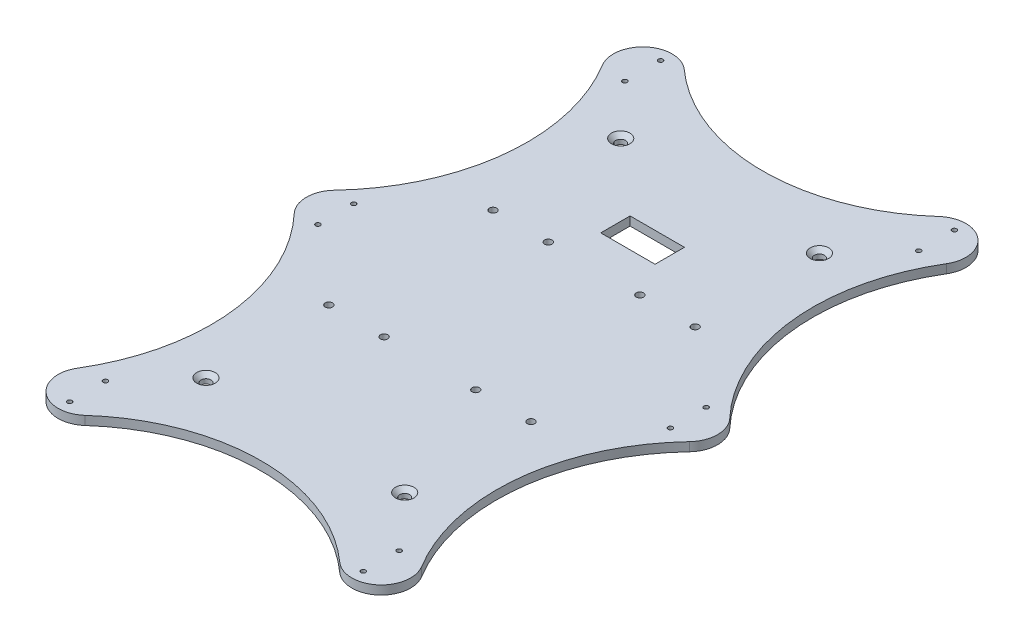
SolidWorks part; units mm, degrees
ref_plane "Front Plane" through (0, 0, 0) normal (0, 0, 1) x (1, 0, 0)
ref_plane "Top Plane" through (0, 0, 0) normal (0, 1, 0) x (1, 0, 0)
ref_plane "Right Plane" through (0, 0, 0) normal (1, 0, 0) x (0, 0, -1)
sketch "Sketch1" plane through (0, 0, 0) normal (0, 1, 0) x (1, 0, 0)
  line L0 (0, 85.4011) -> (0, -85.4011) construction
  line L5 (-25, 0) -> (0, 0) construction
  line L7 (-34.4, -27.95) -> (-15.6, -27.95) construction
  line L8 (0, 85.4011) -> (-22.7784, 85.4011) construction
  line L9 (-60, 0) -> (-60, -6.09) construction
  line L10 (-50, 94.5197) -> (-50, 88.4297) construction
  line L11 (-60, 0) -> (-83.5337, 0) construction
  line L12 (-50, 94.5197) -> (-65.6253, 94.5197) construction
  line L21 (-34.4, -27.95) -> (-34.4, 27.95) construction
  line L27 (-34.4, 27.95) -> (-15.6, 27.95) construction
  line L28 (-15.6, -27.95) -> (-15.6, 27.95) construction
  line L31 (-34.4, -27.95) -> (-15.6, 27.95) construction
  line L32 (-34.4, 27.95) -> (-15.6, -27.95) construction
  arc A4 (-43.3281, 101.9685) -> (43.3281, 101.9685) centre (0, 150.342) ccw
  arc A5 (58.5478, 89.3297) -> (43.3281, 101.9685) centre (50, 94.5197) ccw
  arc A6 (67.2725, -6.8637) -> (67.2725, 6.8637) centre (60, 0) ccw
  arc A7 (58.5478, 89.3297) -> (67.2725, 6.8637) centre (117.0279, 53.8223) ccw
  arc A8 (58.5478, -89.3297) -> (67.2725, -6.8637) centre (117.0279, -53.8223) cw
  arc A9 (58.5478, -89.3297) -> (43.3281, -101.9685) centre (50, -94.5197) cw
  arc A10 (-43.3281, -101.9685) -> (43.3281, -101.9685) centre (0, -150.342) cw
  arc A11 (-58.5478, -89.3297) -> (-43.3281, -101.9685) centre (-50, -94.5197) ccw
  arc A12 (-58.5478, -89.3297) -> (-67.2725, -6.8637) centre (-117.0279, -53.8223) ccw
  arc A13 (-58.5478, 89.3297) -> (-67.2725, 6.8637) centre (-117.0279, 53.8223) cw
  arc A14 (-67.2725, -6.8637) -> (-67.2725, 6.8637) centre (-60, 0) cw
  arc A15 (-58.5478, 89.3297) -> (-43.3281, 101.9685) centre (-50, 94.5197) cw
  circle A16 centre (-60, -6.09) radius 0.7937
  circle A17 centre (-50, 88.4297) radius 0.7937
  circle A18 centre (-50, 100.6097) radius 0.7937
  circle A19 centre (-60, 6.09) radius 0.7937
  circle A20 centre (60, 6.09) radius 0.7937
  circle A21 centre (60, -6.09) radius 0.7937
  circle A22 centre (50, 88.4297) radius 0.7937
  circle A23 centre (50, 100.6097) radius 0.7937
  circle A24 centre (50, -88.4297) radius 0.7937
  circle A25 centre (50, -100.6097) radius 0.7937
  circle A26 centre (-50, -88.4297) radius 0.7937
  circle A27 centre (-50, -100.6097) radius 0.7937
  circle A28 centre (-34.4, 27.95) radius 1.25
  circle A29 centre (-15.6, 27.95) radius 1.25
  circle A30 centre (-34.4, -27.95) radius 1.25
  circle A31 centre (-15.6, -27.95) radius 1.25
  circle A32 centre (15.6, -27.95) radius 1.25
  circle A33 centre (34.4, -27.95) radius 1.25
  circle A34 centre (15.6, 27.95) radius 1.25
  circle A35 centre (34.4, 27.95) radius 1.25
  point P0 (-25, 0)
  dimension "D1" = 18.8
  dimension "D3" = 20
  dimension "D4" = 25
  dimension "D7" = 1.5875
  dimension "D8" = 1.5875
  dimension "D14" = 6.09
  dimension "D15" = 6.09
  dimension "D5" = 2.5
  dimension "D13" = 6.09
  dimension "D2" = 55.9
  dimension "D6" = 6.09
  dimension "D9" = 6.09
  dimension "D10" = 6.09
  dimension "D11" = 6.09
  dimension "D12" = 6.09
  dimension "D16" = 6.09
extrude "Boss-Extrude1" add sketch "Sketch1" along normal blind 3
sketch "Sketch2" plane through (0, 3, 0) normal (0, 1, 0) x (1, 0, 0)
  point P0 (33.8292, 70.8368)
  point P1 (-33.8292, 70.8368)
  point P2 (33.8292, -70.3632)
  point P3 (-33.8292, -70.3632)
hole_wizard "CSK for M3 Flat Head Machine Screw1" positions "Sketch3" profile "Sketch4" countersink size "M3" standard "ANSI Metric" end condition through all
sketch "Sketch3" plane through (0, 3, 0) normal (0, 1, 0) x (1, 0, 0)
  point P0 (-33.8292, 70.8368)
  point P3 (33.8292, 70.8368)
  point P6 (-33.8292, -70.3632)
  point P9 (33.8292, -70.3632)
sketch "Sketch4" plane through (-33.8292, 3, -70.8368) normal (1, 0, 0) x (0, 0, 1)
  line L0 (0, 0) -> (0, 3)
  line L1 (0, 3) -> (1.7, 3)
  line L2 (1.7, 3) -> (1.7, 1.45)
  line L3 (1.7, 1.45) -> (3.15, 0)
  line L5 (3.15, 0) -> (0, 0)
  line L6 (-1.7, 1.45) -> (-3.15, 0) construction
  line L11 (0, -6.35) -> (0, 107.95) construction
  dimension "Thru Hole Dia." = 3.4
  dimension "Thru Hole Depth" = 3
  dimension "Near C'Sink Dia." = 6.3
  dimension "Near C'Sink Angle" = 90
sketch "Sketch5" plane through (0, 0, 0) normal (0, -1, 0) x (1, 0, 0)
  line L0 (-0.1332, -42.1103) -> (-0.1332, -47.0633) construction
  line L5 (-9.3832, -49.5868) -> (9.1168, -49.5868)
  line L6 (-9.3832, -49.5868) -> (-9.3832, -39.5868)
  line L7 (-9.3832, -39.5868) -> (9.1168, -39.5868)
  line L8 (9.1168, -49.5868) -> (9.1168, -39.5868)
  line L9 (-9.3832, -49.5868) -> (9.1168, -39.5868) construction
  line L10 (-9.3832, -39.5868) -> (9.1168, -49.5868) construction
  point P0 (-0.1332, -44.5868)
  dimension "D1" = 18.5
  dimension "D2" = 10
extrude "Cut-Extrude1" cut sketch "Sketch5" against normal up to next
